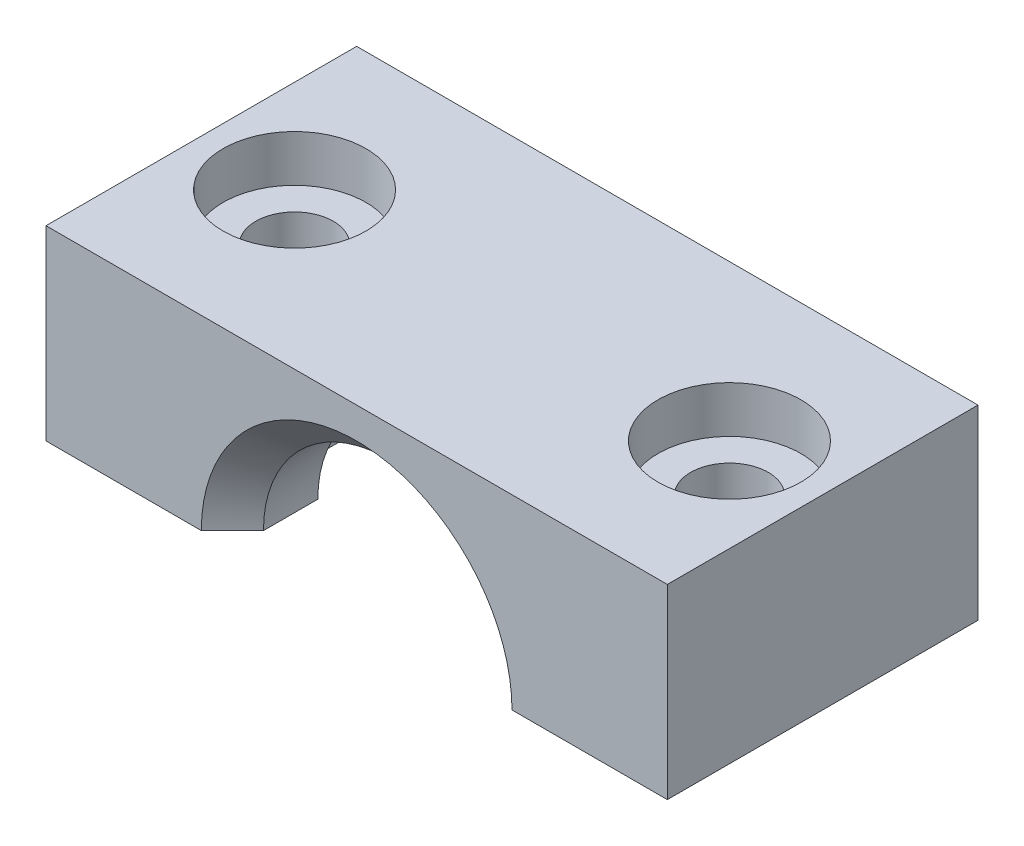
SolidWorks part; units mm, degrees
ref_plane "Спереди" through (0, 0, 0) normal (0, 0, 1) x (1, 0, 0)
ref_plane "Сверху" through (0, 0, 0) normal (0, 1, 0) x (1, 0, 0)
ref_plane "Справа" through (0, 0, 0) normal (1, 0, 0) x (0, 0, -1)
sketch "Эскиз2" plane through (0, 0, 0) normal (0, 0, 1) x (1, 0, 0)
  line L1 (-10, 0) -> (10, 0)
  line L2 (-10, 0) -> (-10, 6)
  line L3 (-10, 6) -> (10, 6)
  line L4 (10, 0) -> (10, 6)
  point P4 (0, 0)
  dimension "D1" = 20
  dimension "D2" = 6
extrude "тело" add sketch "Эскиз2" along normal mid plane 10
sketch "Эскиз3" plane through (0, 0, 5) normal (0, 0, 1) x (1, 0, 0)
  line L0 (-10, 0) -> (10, 0) construction
  circle A0 centre (0, 0) radius 4
  dimension "D1" = 8
extrude "вырез под гайки" cut sketch "Эскиз3" against normal through all
sketch "Эскиз4" plane through (0, 0, 0) normal (0, 0, 1) x (1, 0, 0)
  circle A0 centre (0, 0) radius 5.25
  dimension "D1" = 10.5
extrude "вырез под подшипник" cut sketch "Эскиз4" against normal mid plane 4.5
sketch "Эскиз5" plane through (0, 6, 0) normal (0, 1, 0) x (1, 0, 0)
  line L0 (-7, 0) -> (7, 0) construction
  circle A0 centre (-7, 0) radius 1.25
  circle A1 centre (7, 0) radius 1.25
  point P4 (0, 0)
  dimension "D1" = 2.5
  dimension "D2" = 14
extrude "крепежные отверстия" cut sketch "Эскиз5" against normal through all
chamfer "Фаска2" distance 1 angle 45 2 edges at (0, 4, -5) (0, 4, 5)
sketch "Эскиз6" plane through (0, 6, 0) normal (0, 1, 0) x (1, 0, 0)
  circle A0 centre (-7, 0) radius 2.3
  circle A1 centre (7, 0) radius 2.3
  dimension "D1" = 4.6
extrude "Углубления под шляпки" cut sketch "Эскиз6" against normal blind 1.5
